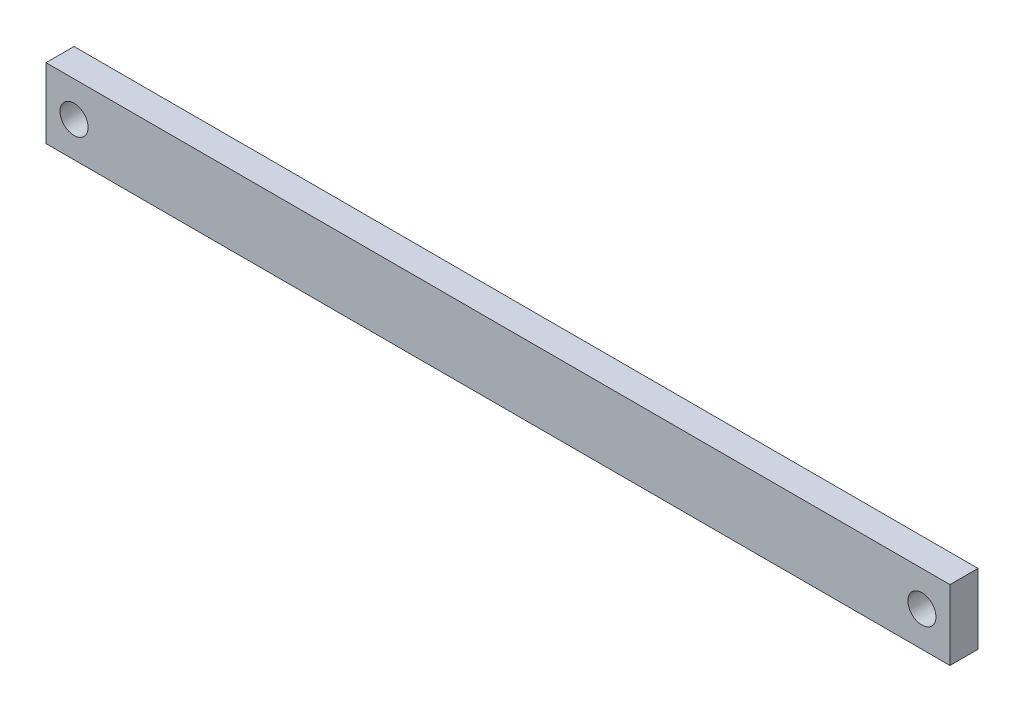
SolidWorks part; units mm, degrees
ref_plane "Front Plane" through (0, 0, 0) normal (0, 0, 1) x (1, 0, 0)
ref_plane "Top Plane" through (0, 0, 0) normal (0, 1, 0) x (1, 0, 0)
ref_plane "Right Plane" through (0, 0, 0) normal (1, 0, 0) x (0, 0, -1)
sketch "Sketch1" plane through (0, 0, 0) normal (0, 0, 1) x (1, 0, 0)
  line L1 (-40.9461, -3.175) -> (40.9461, -3.175)
  line L2 (-40.9461, -3.175) -> (-40.9461, 3.175)
  line L3 (-40.9461, 3.175) -> (40.9461, 3.175)
  line L4 (40.9461, -3.175) -> (40.9461, 3.175)
  dimension "D1" = 6.35
  dimension "D2" = 81.8921
  dimension "D3" = 3.175
  dimension "D4" = 40.9461
extrude "Boss-Extrude1" add sketch "Sketch1" along normal blind 2.54
sketch "Sketch3" plane through (0, 0, 0) normal (0, 0, 1) x (1, 0, 0)
  line L0 (-40.9461, 3.175) -> (-40.9461, -3.175) construction
  circle A0 centre (-38.4061, 0) radius 1.27
  dimension "D2" = 2.54
  dimension "D1" = 2.54
extrude "Cut-Extrude1" cut sketch "Sketch3" along normal through all
mirror "Mirror1" about plane through (0, 0, 0) normal (1, 0, 0) of "Cut-Extrude1"
scale "Scale1" scale about centroid uniform scaling yes scale factor 8
